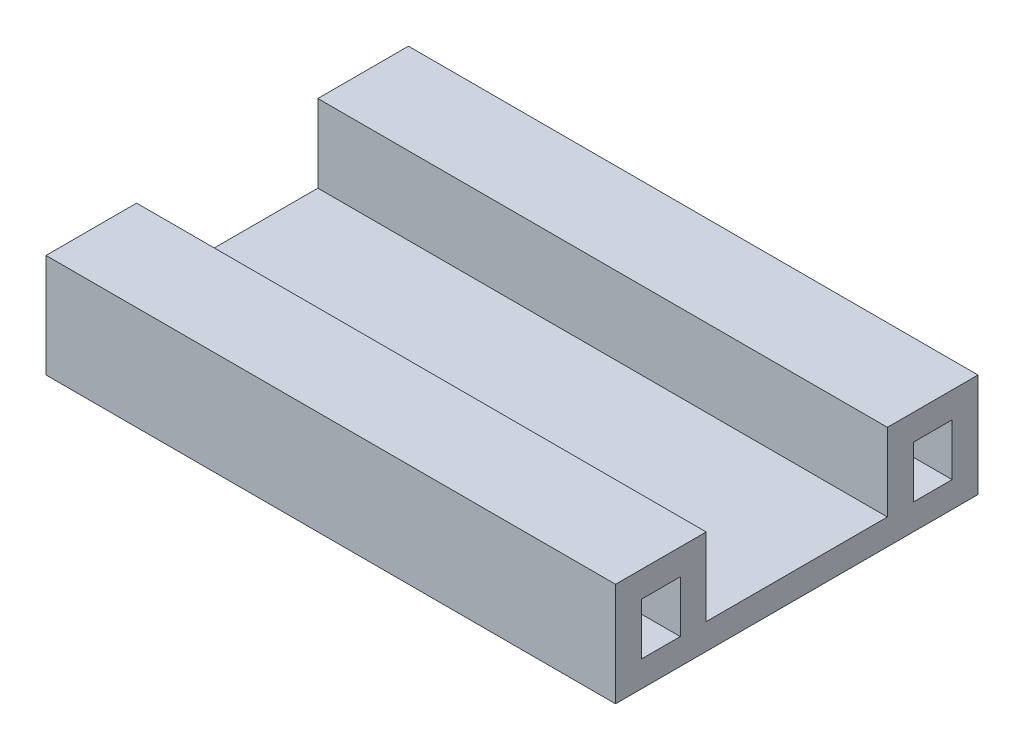
SolidWorks part; units mm, degrees
ref_plane "Front Plane" through (0, 0, 0) normal (0, 0, 1) x (1, 0, 0)
ref_plane "Top Plane" through (0, 0, 0) normal (0, 1, 0) x (1, 0, 0)
ref_plane "Right Plane" through (0, 0, 0) normal (1, 0, 0) x (0, 0, -1)
sketch "Sketch1" plane through (0, 0, 0) normal (0, 1, 0) x (1, 0, 0)
  line L1 (-110, 70) -> (110, 70)
  line L2 (-110, 70) -> (-110, -70)
  line L3 (-110, -70) -> (110, -70)
  line L4 (110, 70) -> (110, -70)
  line L5 (-110, 70) -> (110, -70) construction
  line L6 (-110, -70) -> (110, 70) construction
  point P0 (0, 0)
  dimension "D1" = 140
  dimension "D2" = 220
extrude "Boss-Extrude1" add sketch "Sketch1" along normal blind 10
sketch "Sketch2" plane through (0, 10, 0) normal (0, 1, 0) x (1, 0, 0)
  line L0 (110, -70) -> (110, 70) construction
  line L1 (-110, 60) -> (110, 60)
  line L3 (-110, -60) -> (110, -60)
  line L5 (-110, 60) -> (110, -60) construction
  line L6 (-110, -60) -> (110, 60) construction
  line L7 (110, 70) -> (-110, 70) construction
  line L8 (110, -60) -> (110, -70)
  line L9 (-110, 70) -> (110, 70)
  line L10 (-110, 70) -> (-110, 60)
  line L11 (-110, -70) -> (110, -70)
  line L12 (110, 70) -> (110, 60)
  line L13 (-110, 70) -> (110, -70) construction
  line L14 (-110, -70) -> (110, 70) construction
  line L15 (-110, -60) -> (-110, -70)
  point P0 (0, 0)
  point P10 (0, 0)
  dimension "D1" = 10
extrude "Boss-Extrude2" add sketch "Sketch2" along normal blind 30
sketch "Sketch3" plane through (0, 0, -60) normal (0, 0, 1) x (1, 0, 0)
  line L0 (110, 40) -> (110, 10) construction
  line L1 (-110, 40) -> (110, 40)
  line L2 (-110, 40) -> (-110, 30)
  line L3 (-110, 30) -> (110, 30)
  line L4 (110, 40) -> (110, 30)
  dimension "D1" = 10
extrude "Boss-Extrude3" add sketch "Sketch3" along normal blind 25
mirror "Mirror1" about plane through (0, 0, 0) normal (0, 0, 1) of "Boss-Extrude3"
sketch "Sketch4" plane through (0, 30, 0) normal (0, -1, 0) x (1, 0, 0)
  line L0 (110, -35) -> (110, -60) construction
  line L1 (-110, -35) -> (110, -35)
  line L2 (-110, -35) -> (-110, -45)
  line L3 (-110, -45) -> (110, -45)
  line L4 (110, -35) -> (110, -45)
  dimension "D1" = 10
extrude "Boss-Extrude4" add sketch "Sketch4" along normal up to surface (20 mm away) up to face at (0, 10, 0)
mirror "Mirror2" about plane through (0, 0, 0) normal (0, 0, 1) of "Boss-Extrude4"
sketch "Sketch5" plane through (0, 10, 0) normal (0, 1, 0) x (1, 0, 0)
  line L0 (110, -35) -> (110, 35) construction
  line L1 (-110, 30) -> (110, 30)
  line L2 (-110, 30) -> (-110, -30)
  line L3 (-110, -30) -> (110, -30)
  line L4 (110, 30) -> (110, -30)
  line L5 (-110, 30) -> (110, -30) construction
  line L6 (-110, -30) -> (110, 30) construction
  line L7 (-110, 35) -> (110, 35) construction
  point P0 (0, 0)
  dimension "D1" = 5
extrude "Cut-Extrude1" [suppressed] cut sketch "Sketch5" against normal blind 20
sketch "Sketch6" [suppressed] plane through (0, 10, 0) normal (0, 1, 0) x (1, 0, 0)
  line L1 (-110, 40) -> (110, 40)
  line L2 (-110, 40) -> (-110, 35)
  line L3 (-110, 35) -> (110, 35)
  line L4 (110, 40) -> (110, 35)
extrude "Boss-Extrude5" [suppressed] add sketch "Sketch6" along normal up to surface (30 mm away)
sketch "Sketch7" [suppressed] plane through (-110, 0, 0) normal (-1, 0, 0) x (0, 0, 1)
  line L1 (70, 40) -> (35, 40)
  line L2 (70, 40) -> (70, 0)
  line L3 (70, 0) -> (35, 0)
  line L4 (35, 40) -> (35, 0)
extrude "Cut-Extrude2" [suppressed] cut sketch "Sketch7" against normal up to surface (220 mm away)
